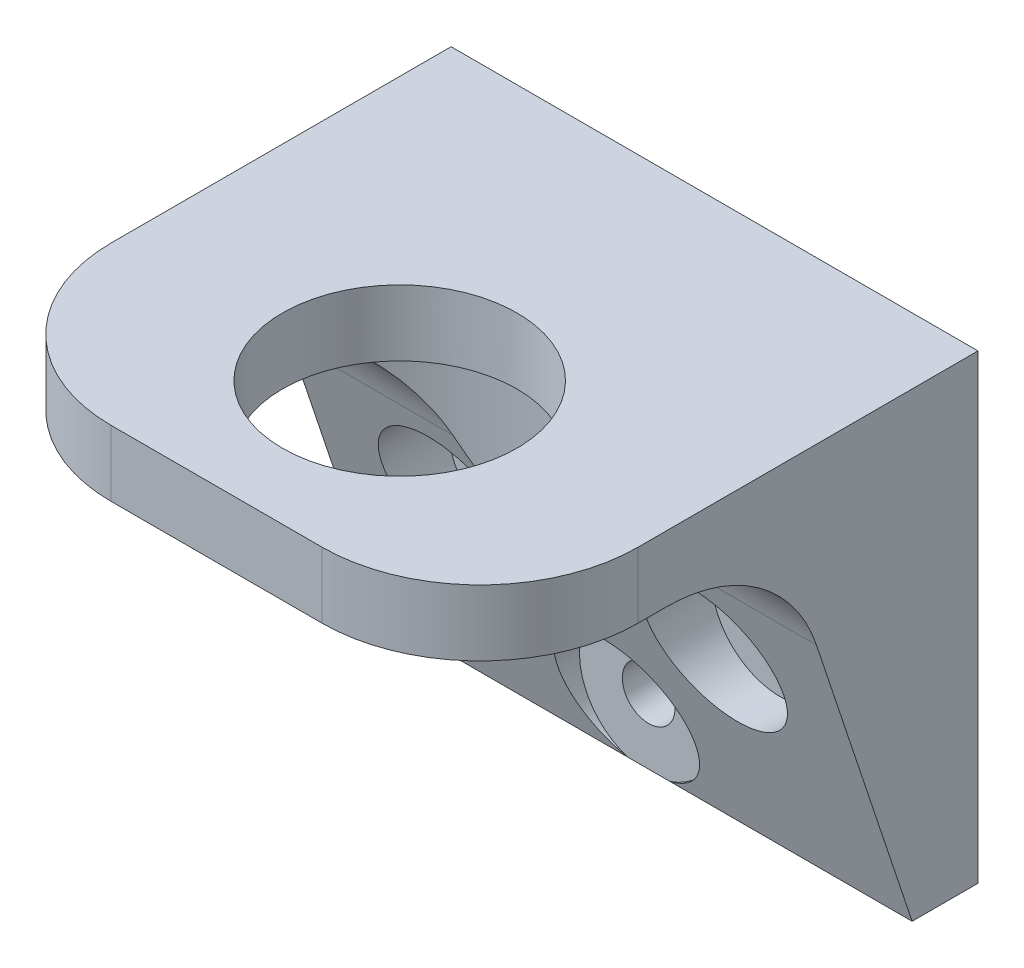
SolidWorks part; units mm, degrees
ref_plane "Front Plane" through (0, 0, 0) normal (0, 0, 1) x (1, 0, 0)
ref_plane "Top Plane" through (0, 0, 0) normal (0, 1, 0) x (1, 0, 0)
ref_plane "Right Plane" through (0, 0, 0) normal (1, 0, 0) x (0, 0, -1)
sketch "Sketch1" plane through (0, 0, 0) normal (0, 0, 1) x (1, 0, 0)
  line L0 (25.4, 6.35) -> (25.4, 35.5898) construction
  line L1 (0, 0) -> (50.8, 0)
  line L2 (0, 0) -> (0, 44.45)
  line L3 (0, 44.45) -> (50.8, 44.45)
  line L4 (50.8, 0) -> (50.8, 44.45)
  point P12 (25.4, 0)
  dimension "D4" = 50.8
  dimension "D5" = 44.45
  dimension "D6" = 6.35
extrude "Boss-Extrude1" add sketch "Sketch1" along normal blind 6.35
sketch "Sketch2" plane through (50.8, 0, 0) normal (1, 0, 0) x (0, 0, -1)
  line L0 (-6.35, 0) -> (-6.35, 44.45)
  line L1 (-6.35, 44.45) -> (-48.006, 44.45)
  line L2 (-48.006, 44.45) -> (-48.006, 38.1)
  line L3 (-48.006, 38.1) -> (-19.05, 38.1)
  line L4 (-19.05, 38.1) -> (-6.35, 0)
  dimension "D1" = 41.656
  dimension "D2" = 12.7
  dimension "D3" = 6.35
extrude "Boss-Extrude2" add sketch "Sketch2" against normal blind 50.8
sketch "Sketch3" plane through (0, 44.45, 0) normal (0, 1, 0) x (1, 0, 0)
  line L0 (0, -48.006) -> (50.8, -48.006) construction
  circle A0 centre (25.4, -30.353) radius 11.303
  dimension "D1" = 22.606
  dimension "D2" = 17.653
extrude "Cut-Extrude1" cut sketch "Sketch3" against normal blind 50.8
sketch "Sketch4" plane through (0, 0, 0) normal (0, 0, -1) x (-1, 0, 0)
  line L0 (0, 0) -> (-50.8, 0) construction
  line L1 (-50.8, 0) -> (-50.8, 44.45) construction
  circle A0 centre (-25.4, 6.35) radius 2.54
  circle A1 centre (-38.1, 19.05) radius 2.54
  circle A2 centre (-12.7, 19.05) radius 2.54
  dimension "D5" = 5.08
  dimension "D1" = 6.35
  dimension "D2" = 12.7
  dimension "D3" = 25.4
  dimension "D4" = 12.7
  dimension "D6" = 25.4
extrude "Cut-Extrude2" cut sketch "Sketch4" against normal blind 50.8
sketch "Sketch5" plane through (0, 0, 48.006) normal (0, 0, 1) x (1, 0, 0)
  circle A0 centre (12.7, 19.05) radius 6.6675
  circle A1 centre (38.1, 19.05) radius 6.6675
  circle A2 centre (25.4, 6.35) radius 6.6675
  dimension "D1" = 13.335
extrude "Cut-Extrude3" cut sketch "Sketch5" against normal blind 41.656
sketch "Sketch6" plane through (0, 38.1, 0) normal (0, -1, 0) x (1, 0, 0)
  circle A1 centre (25.4, 30.353) radius 17.653
extrude "Cut-Extrude4" cut sketch "Sketch6" along normal blind 50.8
fillet "Fillet1" radius 15.24 4 edges at (5.9201, 38.1, 19.05) (44.8799, 38.1, 19.05) (50.8, 41.275, 48.006) (0, 41.275, 48.006)
